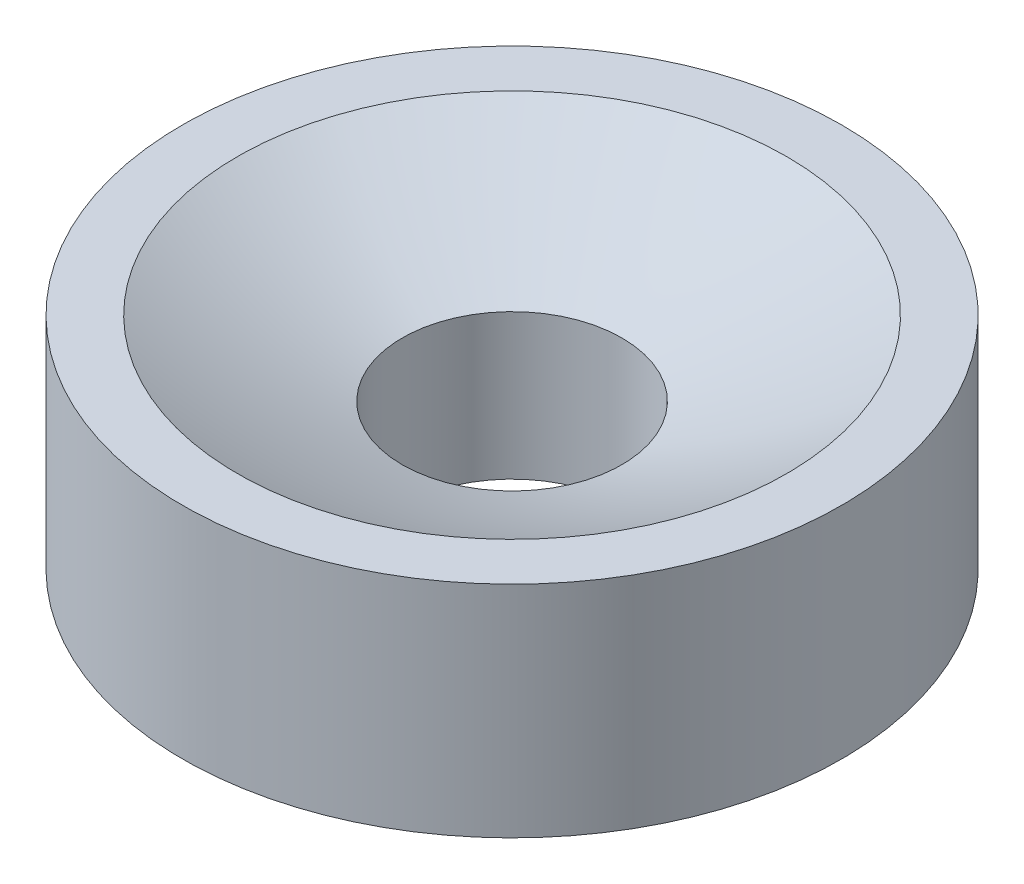
SolidWorks part; units mm, degrees
material "AISI 1020"
ref_plane "Front Plane" through (0, 0, 0) normal (0, 0, 1) x (1, 0, 0)
ref_plane "Top Plane" through (0, 0, 0) normal (0, 1, 0) x (1, 0, 0)
ref_plane "Right Plane" through (0, 0, 0) normal (1, 0, 0) x (0, 0, -1)
sketch "Sketch1" plane through (0, 0, 0) normal (0, 1, 0) x (1, 0, 0)
  circle A0 centre (0, 0) radius 6
  circle A1 centre (0, 0) radius 2
  dimension "D1" = 12
  dimension "D2" = 4
extrude "Boss-Extrude1" [suppressed] add sketch "Sketch1" along normal blind 4
sketch "Sketch2" [suppressed] plane through (0, 0, 0) normal (0, 0, 1) x (1, 0, 0)
  line L5 (0, 5.0209) -> (0, -0.2235) construction
  line L6 (0, 2.1424) -> (5.3724, 2.1424)
  line L7 (5.3724, 2.1424) -> (5.3724, 4)
  line L8 (6, 4) -> (-6, 4) construction
  line L9 (5.3724, 4) -> (4.0566, 3.7889)
  line L12 (2.1357, 3.0712) -> (0, 3.0712)
  line L13 (0, 3.0712) -> (0, 2.1424)
  line L14 (2.3454, 3.0712) -> (2.1357, 3.0712)
  spline S0 degree 3 poles (4.0566, 3.7889) (3.441, 3.6632) (2.9067, 3.3324) (2.3454, 3.0712) knots 0 0 0 0 1 1 1 1
revolve "Cut-Revolve5" [suppressed] cut sketch "Sketch2" angle 360 about L5
sketch "Sketch3" [suppressed] plane through (0, 4, 0) normal (0, 1, 0) x (1, 0, 0)
  circle A0 centre (0, 0) radius 5.4033
extrude "Cut-Extrude1" [suppressed] cut sketch "Sketch3" against normal blind 3
sketch "Sketch4" plane through (0, 0, 0) normal (0, 0, 1) x (1, 0, 0)
  line L0 (0, 0) -> (6, 0)
  line L1 (6, 0) -> (6, 4)
  line L2 (6, 4) -> (5, 4)
  line L3 (0, 0) -> (0, 2)
  spline S0 degree 2 poles (0, 2) (2.6166, 2.7117) (5, 4) knots 0 0 0 1 1 1
  dimension "D1" = 6
  dimension "D2" = 4
  dimension "D3" = 1
  dimension "D4" = 2
revolve "Revolve1" add sketch "Sketch4" angle 360 about L3
sketch "Sketch5" plane through (0, 0, 0) normal (0, 1, 0) x (1, 0, 0)
  circle A0 centre (0, 0) radius 2
  dimension "D1" = 4
extrude "Cut-Extrude4" cut sketch "Sketch5" along normal blind 13
